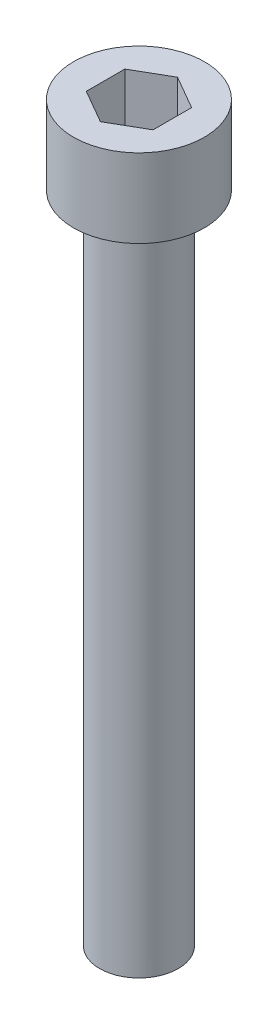
SolidWorks part; units mm, degrees
ref_plane "Спереди" through (0, 0, 0) normal (0, 0, 1) x (1, 0, 0)
ref_plane "Сверху" through (0, 0, 0) normal (0, 1, 0) x (1, 0, 0)
ref_plane "Справа" through (0, 0, 0) normal (1, 0, 0) x (0, 0, -1)
sketch "Эскиз1" plane through (0, 0, 0) normal (0, 1, 0) x (1, 0, 0)
  line L1 (0, -2.9445) -> (2.55, -1.4722)
  line L2 (2.55, -1.4722) -> (2.55, 1.4722)
  line L3 (2.55, 1.4722) -> (0, 2.9445)
  line L4 (0, 2.9445) -> (-2.55, 1.4722)
  line L5 (-2.55, 1.4722) -> (-2.55, -1.4722)
  line L6 (-2.55, -1.4722) -> (0, -2.9445)
  circle A0 centre (0, 0) radius 5
  circle A1 centre (0, 0) radius 2.55 construction
  dimension "D1" = 5.1
extrude "Вытянуть1" add sketch "Эскиз1" along normal blind 6
sketch "Эскиз2" plane through (0, 0, 0) normal (0, -1, 0) x (1, 0, 0)
  circle A0 centre (0, 0) radius 3
extrude "Вытянуть2" add sketch "Эскиз2" along normal blind 50
